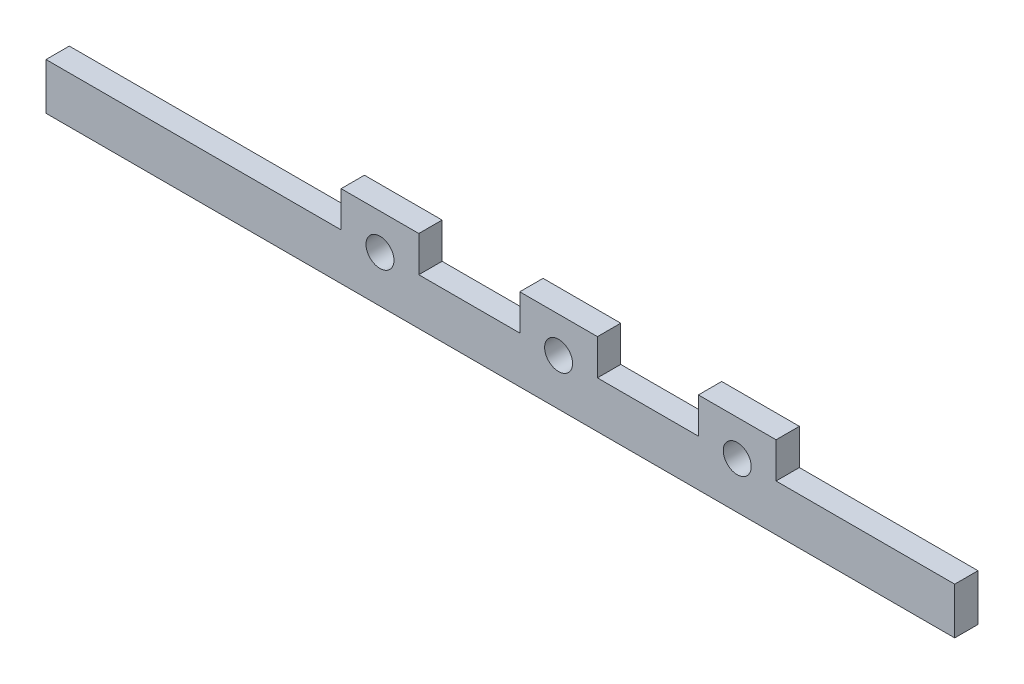
SolidWorks part; units mm, degrees
ref_plane "Alzado" through (0, 0, 0) normal (0, 0, 1) x (1, 0, 0)
ref_plane "Planta" through (0, 0, 0) normal (0, 1, 0) x (1, 0, 0)
ref_plane "Vista lateral" through (0, 0, 0) normal (1, 0, 0) x (0, 0, -1)
sketch "Croquis1" plane through (0, 0, 0) normal (0, 0, 1) x (1, 0, 0)
  line L0 (-292.5, 0) -> (292.5, 0)
  line L1 (-102.5, 30) -> (-292.5, 30)
  line L2 (12.5, 30) -> (12.5, 53)
  line L3 (12.5, 53) -> (62.5, 53)
  line L4 (62.5, 30) -> (62.5, 53)
  line L5 (177.5, 30) -> (292.5, 30)
  line L6 (-102.5, 30) -> (-102.5, 53)
  line L7 (-102.5, 53) -> (-52.5, 53)
  line L8 (-52.5, 30) -> (-52.5, 53)
  line L9 (12.5, 30) -> (-52.5, 30)
  line L10 (-292.5, 0) -> (-292.5, 30)
  line L11 (-102.5, 30) -> (-77.5, 30) construction
  line L12 (127.5, 30) -> (127.5, 53)
  line L13 (62.5, 30) -> (127.5, 30)
  line L14 (292.5, 0) -> (292.5, 30)
  line L15 (127.5, 53) -> (177.5, 53)
  line L16 (177.5, 30) -> (177.5, 53)
  line L17 (12.5, 30) -> (37.5, 30) construction
  line L18 (127.5, 30) -> (152.5, 30) construction
  line L19 (37.5, 30) -> (37.5, 0) construction
  circle A0 centre (37.5, 30) radius 9
  circle A1 centre (-77.5, 30) radius 9
  circle A2 centre (152.5, 30) radius 9
  point P0 (0, 0)
  dimension "D8" = 18
  dimension "D1" = 585
  dimension "D2" = 330
  dimension "D4" = 65
  dimension "D5" = 30
  dimension "D6" = 25
  dimension "D7" = 53
  dimension "D9" = 50
  dimension "D10" = 65
extrude "Saliente-Extruir1" add sketch "Croquis1" along normal blind 15
